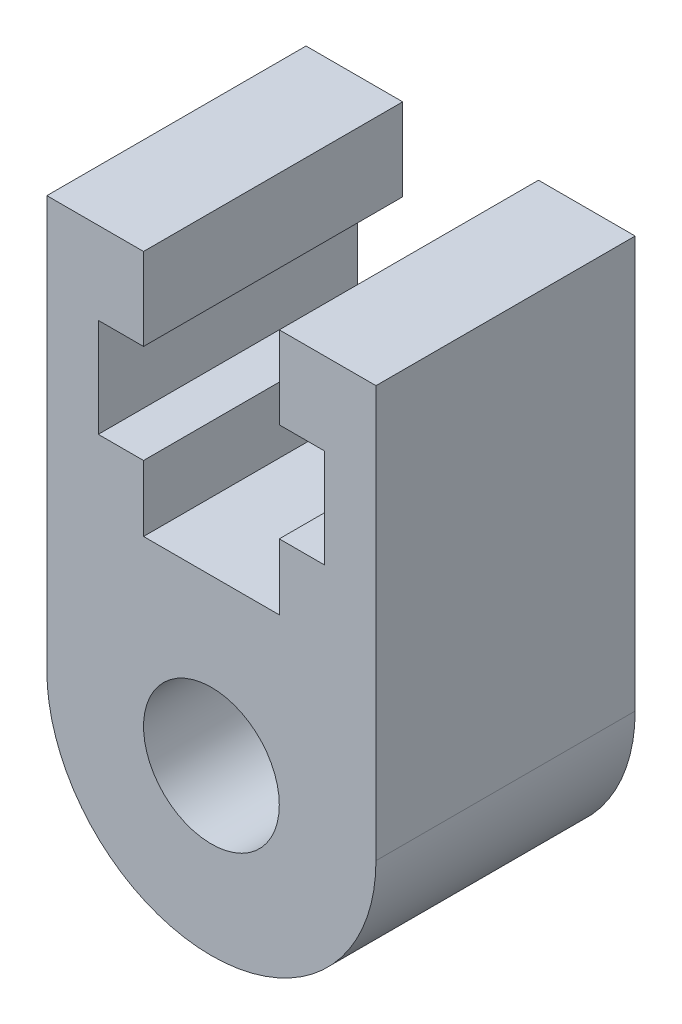
SolidWorks part; units mm, degrees
ref_plane "Front Plane" through (0, 0, 0) normal (0, 0, 1) x (1, 0, 0)
ref_plane "Top Plane" through (0, 0, 0) normal (0, 1, 0) x (1, 0, 0)
ref_plane "Right Plane" through (0, 0, 0) normal (1, 0, 0) x (0, 0, -1)
sketch "Sketch1" plane through (0, 0, 0) normal (0, 0, 1) x (1, 0, 0)
  line L0 (-4, 0) -> (-4, 10)
  line L1 (-4, 10) -> (-1.65, 10)
  line L2 (-1.65, 10) -> (-1.65, 8)
  line L3 (-1.65, 8) -> (-2.75, 8)
  line L4 (-2.75, 8) -> (-2.75, 5.6)
  line L5 (-2.75, 5.6) -> (-1.65, 5.6)
  line L6 (-1.65, 5.6) -> (-1.65, 4)
  line L7 (-1.65, 4) -> (1.65, 4)
  line L8 (0, 0) -> (0, 4) construction
  line L9 (1.65, 5.6) -> (1.65, 4)
  line L10 (2.75, 5.6) -> (1.65, 5.6)
  line L11 (2.75, 8) -> (2.75, 5.6)
  line L12 (1.65, 8) -> (2.75, 8)
  line L13 (1.65, 10) -> (1.65, 8)
  line L14 (4, 10) -> (1.65, 10)
  line L15 (4, 0) -> (4, 10)
  circle A0 centre (0, 0) radius 1.65
  arc A1 (-4, 0) -> (4, 0) centre (0, 0) ccw
  dimension "D1" = 3.3
  dimension "D2" = 4
  dimension "D3" = 1.65
  dimension "D4" = 2.4
  dimension "D5" = 2.75
  dimension "D6" = 2
  dimension "D7" = 6
  dimension "D8" = 10
extrude "Boss-Extrude1" add sketch "Sketch1" along normal blind 6.3
